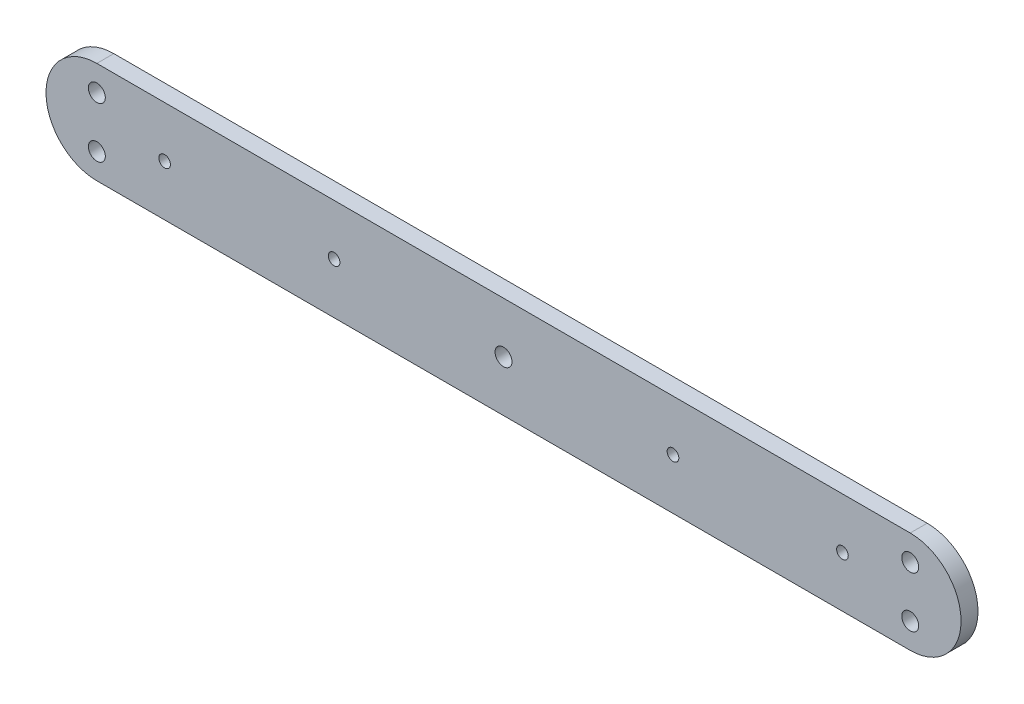
SolidWorks part; units mm, degrees
ref_plane "Front Plane" through (0, 0, 0) normal (0, 0, 1) x (1, 0, 0)
ref_plane "Top Plane" through (0, 0, 0) normal (0, 1, 0) x (1, 0, 0)
ref_plane "Right Plane" through (0, 0, 0) normal (1, 0, 0) x (0, 0, -1)
sketch "Sketch1" plane through (0, 0, 0) normal (0, 0, 1) x (1, 0, 0)
  line L0 (-89.2432, 0) -> (215.5568, 0) construction
  line L1 (-89.2432, 19.05) -> (215.5568, 19.05)
  line L2 (-89.2432, -19.05) -> (215.5568, -19.05)
  line L3 (-89.2432, 0) -> (-89.2432, -9.525) construction
  line L4 (-89.2432, -9.525) -> (215.5568, -9.525) construction
  line L5 (215.5568, -9.525) -> (215.5568, 9.525) construction
  line L6 (215.5568, 9.525) -> (-89.2432, 9.525) construction
  line L7 (-89.2432, 9.525) -> (-89.2432, 0) construction
  arc A0 (-89.2432, 19.05) -> (-89.2432, -19.05) centre (-89.2432, 0) ccw
  arc A1 (215.5568, -19.05) -> (215.5568, 19.05) centre (215.5568, 0) ccw
  circle A3 centre (63.1568, 0) radius 3.175
  circle A5 centre (-0.3432, 0) radius 2.1828
  circle A6 centre (126.6568, 0) radius 2.1828
  circle A7 centre (215.5568, -9.525) radius 3.175
  circle A8 centre (215.5568, 9.525) radius 3.175
  circle A9 centre (-89.2432, 9.525) radius 3.175
  circle A10 centre (-89.2432, -9.525) radius 3.175
  circle A11 centre (-63.8432, 0) radius 2.1828
  circle A12 centre (190.1568, 0) radius 2.1828
  point P3 (63.1568, 0)
  dimension "D3" = 6.35
  dimension "D4" = 6.35
  dimension "D5" = 6.35
  dimension "D6" = 127
  dimension "D7" = 6.35
  dimension "D8" = 4.3656
  dimension "D9" = 4.3656
  dimension "D10" = 9.525
  dimension "D12" = 6.35
  dimension "D14" = 4.3656
  dimension "D15" = 4.3656
  dimension "D17" = 25.4
  dimension "D1" = 304.8
  dimension "D2" = 38.1
  dimension "D11" = 9.525
  dimension "D13" = 88.9
  dimension "D16" = 25.4
extrude "Boss-Extrude1" add sketch "Sketch1" along normal blind 6.35
